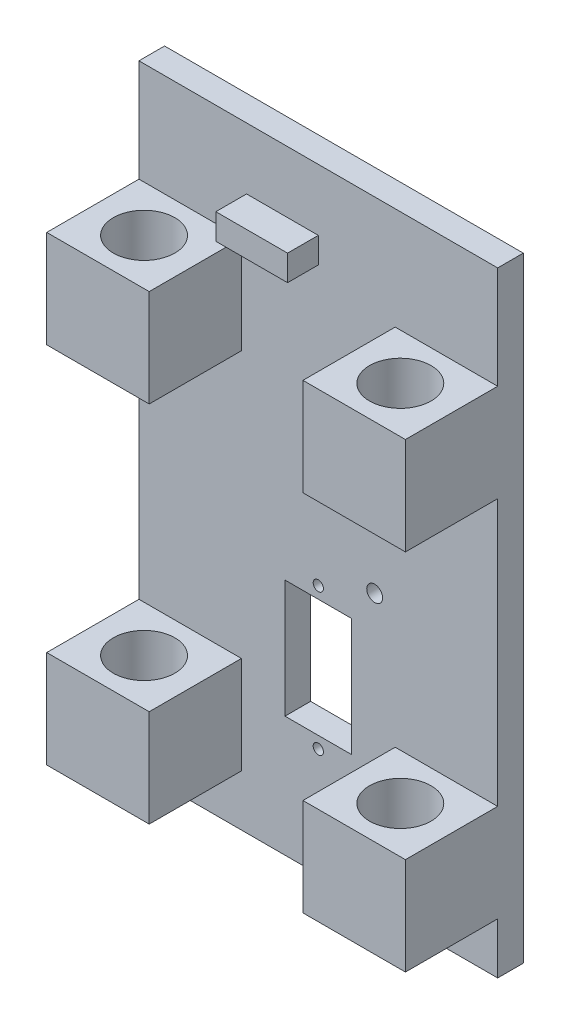
SolidWorks part; units mm, degrees
ref_plane "Front" through (0, 0, 0) normal (0, 0, 1) x (1, 0, 0)
ref_plane "Top" through (0, 0, 0) normal (0, 1, 0) x (1, 0, 0)
ref_plane "Right" through (0, 0, 0) normal (1, 0, 0) x (0, 0, -1)
sketch "Sketch1" plane through (0, 0, 0) normal (0, 0, 1) x (1, 0, 0)
  line L1 (-35, -60) -> (35, -60)
  line L2 (-35, -60) -> (-35, 60)
  line L3 (-35, 60) -> (35, 60)
  line L4 (35, -60) -> (35, 60)
  line L5 (-35, -60) -> (35, 60) construction
  line L6 (-35, 60) -> (35, -60) construction
  point P0 (0, 0)
  dimension "D1" = 120
  dimension "D2" = 70
extrude "Boss-Extrude1" add sketch "Sketch1" along normal blind 5
sketch "Sketch2" plane through (0, 0, 5) normal (0, 0, 1) x (1, 0, 0)
  line L0 (-35, 60) -> (-35, -60) construction
  line L1 (-35, 40) -> (-15, 40)
  line L2 (-35, 40) -> (-35, 21)
  line L3 (-35, 21) -> (-15, 21)
  line L4 (-15, 40) -> (-15, 21)
  line L5 (-35, 40) -> (-15, 21) construction
  line L6 (-35, 21) -> (-15, 40) construction
  line L7 (35, -60) -> (35, 60) construction
  line L8 (35, 40) -> (15, 40)
  line L9 (35, 40) -> (35, 21)
  line L10 (35, 21) -> (15, 21)
  line L11 (15, 40) -> (15, 21)
  line L12 (35, 40) -> (15, 21) construction
  line L13 (35, 21) -> (15, 40) construction
  line L14 (35, 60) -> (-35, 60) construction
  line L15 (-35, -31) -> (-15, -31)
  line L16 (-35, -31) -> (-35, -50)
  line L17 (-35, -50) -> (-15, -50)
  line L18 (-15, -31) -> (-15, -50)
  line L19 (-35, -31) -> (-15, -50) construction
  line L20 (-35, -50) -> (-15, -31) construction
  line L21 (35, -31) -> (15, -31)
  line L22 (35, -31) -> (35, -50)
  line L23 (35, -50) -> (15, -50)
  line L24 (15, -31) -> (15, -50)
  line L25 (35, -31) -> (15, -50) construction
  line L26 (35, -50) -> (15, -31) construction
  line L27 (-35, -60) -> (35, -60) construction
  point P4 (-25, 30.5)
  point P11 (25, 30.5)
  point P18 (-25, -40.5)
  point P23 (25, -40.5)
  dimension "D1" = 19
  dimension "D2" = 20
  dimension "D3" = 19
  dimension "D4" = 20
  dimension "D5" = 19
  dimension "D6" = 20
  dimension "D7" = 19
  dimension "D8" = 20
  dimension "D9" = 20
  dimension "D10" = 10
extrude "Boss-Extrude2" add sketch "Sketch2" along normal blind 18
sketch "Sketch3" plane through (0, 40, 0) normal (0, 1, 0) x (1, 0, 0)
  line L0 (-25, -23) -> (-25, -5) construction
  line L1 (-15, -23) -> (-35, -23) construction
  line L2 (-15, -5) -> (-35, -5) construction
  line L3 (25, -23) -> (25, -5) construction
  line L4 (35, -23) -> (15, -23) construction
  line L5 (35, -5) -> (15, -5) construction
  circle A0 centre (-25, -14) radius 6
  circle A1 centre (25, -14) radius 6
  dimension "D1" = 12
  dimension "D2" = 12
extrude "Cut-Extrude1" cut sketch "Sketch3" against normal through all
sketch "Sketch4" plane through (0, 0, 0) normal (0, 0, -1) x (-1, 0, 0)
  line L0 (35, 60) -> (35, -60) construction
  line L1 (-6.5, -36.5) -> (6.5, -36.5)
  line L2 (-6.5, -36.5) -> (-6.5, -13.5)
  line L3 (-6.5, -13.5) -> (6.5, -13.5)
  line L4 (6.5, -36.5) -> (6.5, -13.5)
  line L5 (-6.5, -36.5) -> (6.5, -13.5) construction
  line L6 (-6.5, -13.5) -> (6.5, -36.5) construction
  line L7 (-35, 60) -> (35, 60) construction
  circle A0 centre (0, -11.2) radius 1
  circle A1 centre (0, -38.8) radius 1
  point P0 (0, -25)
  dimension "D5" = 2
  dimension "D6" = 2.3
  dimension "D7" = 2
  dimension "D8" = 2.3
  dimension "D1" = 23
  dimension "D2" = 13
  dimension "D3" = 35
  dimension "D4" = 85
  dimension "D9" = 6.5
extrude "Cut-Extrude2" cut sketch "Sketch4" against normal up to next
sketch "Sketch5" plane through (0, 0, 5) normal (0, 0, 1) x (1, 0, 0)
  line L5 (-35, 60) -> (-35, 40) construction
  line L6 (-14, 48) -> (0, 48)
  line L8 (-14, 48) -> (-14, 43)
  line L9 (-14, 43) -> (0, 43)
  line L10 (0, 48) -> (0, 43)
  line L11 (-14, 48) -> (0, 43) construction
  line L12 (-14, 43) -> (0, 48) construction
  line L13 (35, 60) -> (-35, 60) construction
  point P0 (-7, 45.5)
  dimension "D1" = 5
  dimension "D2" = 14
  dimension "D3" = 21
  dimension "D4" = 12
extrude "Boss-Extrude3" add sketch "Sketch5" along normal blind 6
sketch "Sketch6" plane through (0, 0, 0) normal (0, 0, -1) x (-1, 0, 0)
  line L0 (-35, -60) -> (-35, 60) construction
  line L1 (35, -60) -> (-35, -60) construction
  circle A0 centre (-11, -7) radius 1.55
  circle A1 centre (-11, -43) radius 1.55
  dimension "D1" = 3.1
  dimension "D2" = 3.1
  dimension "D3" = 24
  dimension "D4" = 17
  dimension "D5" = 36
extrude "Cut-Extrude3" cut sketch "Sketch6" against normal through all
